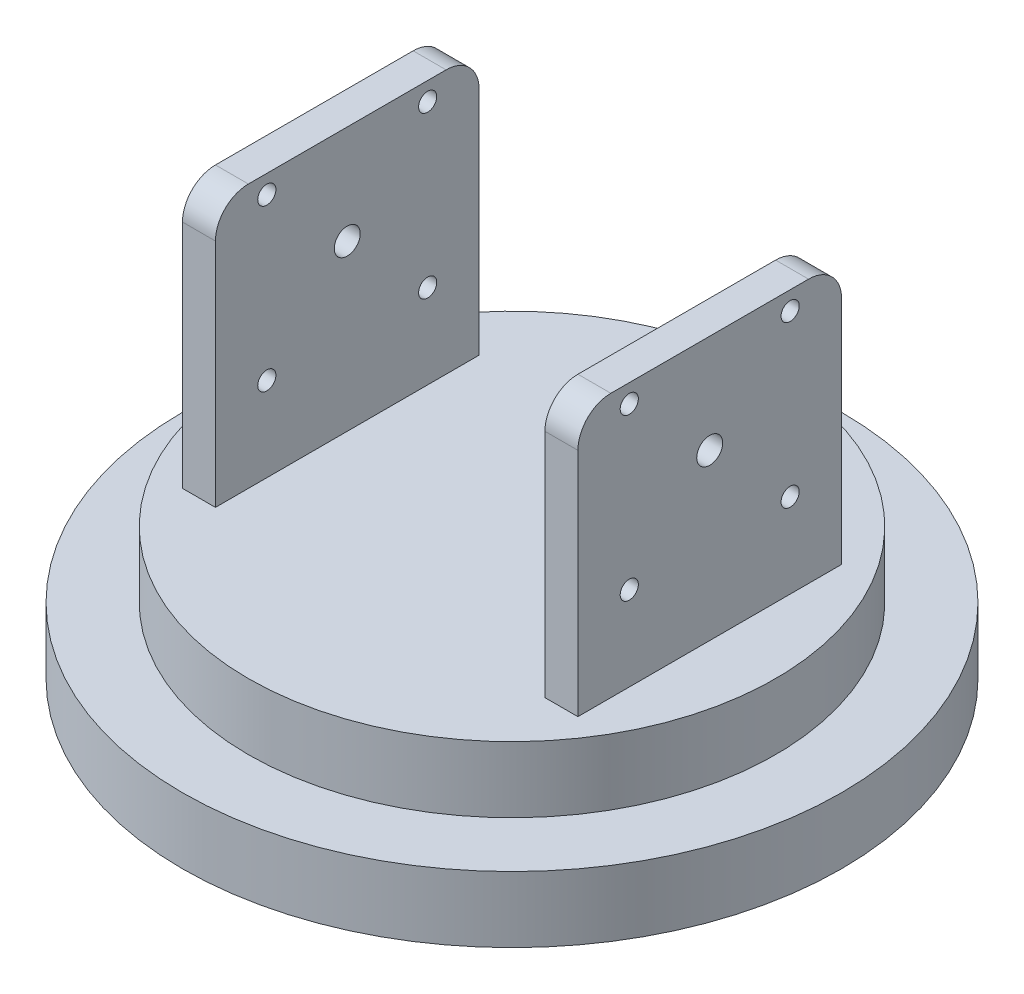
SolidWorks part; units mm, degrees
material "Plain Carbon Steel"
ref_plane "Front Plane" through (0, 0, 0) normal (0, 0, 1) x (1, 0, 0)
ref_plane "Top Plane" through (0, 0, 0) normal (0, 1, 0) x (1, 0, 0)
ref_plane "Right Plane" through (0, 0, 0) normal (1, 0, 0) x (0, 0, -1)
sketch "Sketch2" plane through (0, 0, 0) normal (0, 1, 0) x (1, 0, 0)
  circle A1 centre (0, 0) radius 63.5
  dimension "D2" = 127
extrude "Boss-Extrude1" add sketch "Sketch2" along normal blind 12.7
sketch "Sketch3" plane through (0, 12.7, 0) normal (0, 1, 0) x (1, 0, 0)
  circle A0 centre (0, 0) radius 50.8
  dimension "D1" = 101.6
extrude "Boss-Extrude2" add sketch "Sketch3" along normal blind 12.7
sketch "Sketch4" plane through (0, 0, 0) normal (0, -1, 0) x (1, 0, 0)
  circle A0 centre (0, 0) radius 6.35
  dimension "D1" = 12.7
extrude "Boss-Extrude3" add sketch "Sketch4" along normal blind 25.4
sketch "Sketch5" plane through (0, 25.4, 0) normal (0, 1, 0) x (1, 0, 0)
  line L0 (0, 0) -> (0, 17.7689) construction
  line L1 (38.1, -25.4) -> (31.75, -25.4)
  line L2 (-38.1, 25.4) -> (-31.75, 25.4)
  line L3 (-38.1, 25.4) -> (-38.1, -25.4)
  line L4 (-38.1, -25.4) -> (-31.75, -25.4)
  line L5 (-31.75, 25.4) -> (-31.75, -25.4)
  line L6 (31.75, 25.4) -> (31.75, -25.4)
  line L7 (38.1, 25.4) -> (31.75, 25.4)
  line L8 (38.1, 25.4) -> (38.1, -25.4)
  dimension "D1" = 6.35
  dimension "D2" = 50.8
  dimension "D3" = 25.4
  dimension "D4" = 31.75
extrude "Boss-Extrude4" add sketch "Sketch5" along normal blind 50.8
fillet "Fillet1" radius 6.35 4 edges at (34.925, 76.2, 25.4) (-34.925, 76.2, 25.4) (34.925, 76.2, -25.4) (-34.925, 76.2, -25.4)
sketch "Sketch6" plane through (-38.1, 0, 0) normal (-1, 0, 0) x (0, 0, 1)
  line L0 (-19.05, 76.2) -> (19.05, 76.2) construction
  line L1 (25.4, 69.85) -> (25.4, 25.4) construction
  circle A0 centre (0, 57.15) radius 2.5019
  circle A1 centre (-15.5, 41.65) radius 1.75
  circle A2 centre (15.5, 41.65) radius 1.75
  circle A3 centre (15.5, 72.65) radius 1.75
  circle A4 centre (-15.5, 72.65) radius 1.75
  point P10 (0, 0)
  point P11 (0, 0)
  point P17 (0, 0)
  point P18 (1.7887, 55.4007)
  dimension "D1" = 5.0038
  dimension "D2" = 19.05
  dimension "D3" = 25.4
  dimension "D5" = 15.5
  dimension "D6" = 15.5
  dimension "D7" = 3.5
  dimension "D10" = 31
  dimension "D11" = 31
  dimension "D12" = 9.9
  dimension "D8" = 2
  dimension "D9" = 2
extrude "Cut-Extrude1" cut sketch "Sketch6" against normal through all
sketch "Sketch7" plane through (0, -25.4, 0) normal (0, -1, 0) x (1, 0, 0)
  line L7 (0, 0) -> (0, 6.35) construction
  line L8 (0, 5.08) -> (0.7102, 6.3102)
  line L9 (0, 5.08) -> (-0.7102, 6.3102)
  arc A6 (0.7102, 6.3102) -> (-0.7102, 6.3102) centre (0, 0) ccw
  dimension "D1" = 30
  dimension "D2" = 6.35
  dimension "D3" = 1.4205
  dimension "D4" = 1.4205
extrude "Cut-Extrude2" cut sketch "Sketch7" against normal blind 12.7
pattern_circular "CirPattern1" count 28 over 360 about axis through (0, 0, 0) along (0, 1, 0) of "Cut-Extrude2"
